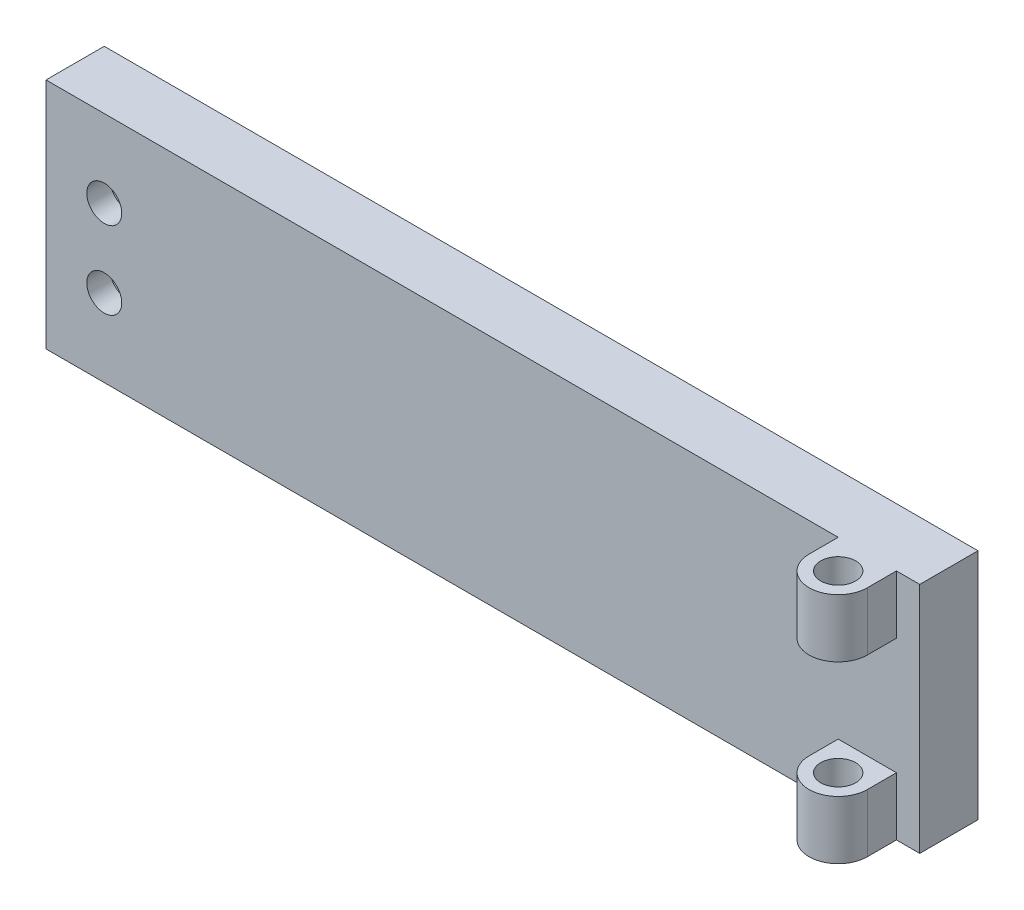
SolidWorks part; units mm, degrees
material "ABS"
ref_plane "Plan de face" through (0, 0, 0) normal (0, 0, 1) x (1, 0, 0)
ref_plane "Plan de dessus" through (0, 0, 0) normal (0, 1, 0) x (1, 0, 0)
ref_plane "Plan de droite" through (0, 0, 0) normal (1, 0, 0) x (0, 0, -1)
sketch "Esquisse1" plane through (0, 0, 0) normal (0, 0, 1) x (1, 0, 0)
  line L1 (0, 0) -> (75, 0)
  line L2 (0, 0) -> (0, 20)
  line L3 (0, 20) -> (75, 20)
  line L4 (75, 0) -> (75, 20)
  dimension "D1" = 75
  dimension "D2" = 20
extrude "Boss.-Extru.1" add sketch "Esquisse1" along normal blind 5
sketch "Esquisse2" plane through (0, 0, 5) normal (0, 0, 1) x (1, 0, 0)
  line L0 (0, 20) -> (68, 20) construction
  line L1 (75, 20) -> (0, 20) construction
  line L2 (0, 0) -> (75, 0) construction
  line L3 (68, 20) -> (73, 20)
  line L4 (68, 20) -> (68, 15)
  line L5 (68, 15) -> (73, 15)
  line L6 (73, 20) -> (73, 15)
  line L7 (68, 0) -> (73, 0)
  line L8 (68, 0) -> (68, 5)
  line L9 (68, 5) -> (73, 5)
  line L10 (73, 0) -> (73, 5)
  dimension "D1" = 68
  dimension "D2" = 5
  dimension "D3" = 5
extrude "Boss.-Extru.2" add sketch "Esquisse2" along normal blind 5
sketch "Esquisse3" plane through (0, 0, 0) normal (0, -1, 0) x (1, 0, 0)
  line L0 (68, 10) -> (68, 5) construction
  line L1 (73, 10) -> (73, 5) construction
  line L2 (68, 7.5) -> (68, 10)
  line L3 (68, 10) -> (70.5, 10)
  line L4 (70.5, 10) -> (73, 10)
  line L5 (73, 10) -> (73, 7.5)
  arc A0 (68, 7.5) -> (73, 7.5) centre (70.5, 7.5) cw
  circle A1 centre (70.5, 7.5) radius 1.5
  line M4 (73, 5) -> (73, 10)
  line M5 (73, 10) -> (68, 10)
  line M6 (68, 10) -> (68, 5)
  dimension "D1" = 3
extrude "Enlèv. mat.-Extru.1" cut sketch "Esquisse3" against normal through all contours A1 | A0 M6 M5 | A0 M5 M4
sketch "Esquisse4" plane through (0, 0, 0) normal (0, 0, -1) x (-1, 0, 0)
  line L0 (0, 0) -> (-5, 0) construction
  line L1 (0, 0) -> (-75, 0) construction
  line L2 (-5, 0) -> (-5, 6.6667) construction
  line L3 (-5, 6.6667) -> (-5, 13.3333) construction
  line L4 (-5, 13.3333) -> (-5, 20) construction
  line L5 (-75, 20) -> (0, 20) construction
  circle A0 centre (-5, 6.6667) radius 1.5
  circle A1 centre (-5, 13.3333) radius 1.5
  dimension "D2" = 3
  dimension "D1" = 5
extrude "Enlèv. mat.-Extru.2" cut sketch "Esquisse4" against normal through all
sketch "Esquisse5" plane through (0, 0, 0) normal (0, 0, -1) x (-1, 0, 0)
  circle A0 centre (-5, 6.6667) radius 3
  circle A1 centre (-5, 13.3333) radius 3
  dimension "D1" = 6
extrude "Enlèv. mat.-Extru.3" cut sketch "Esquisse5" against normal blind 3
